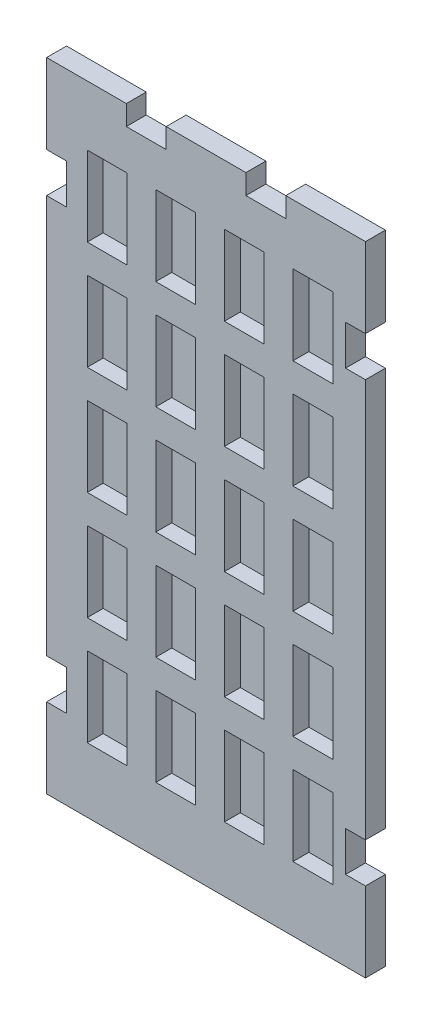
SolidWorks part; units mm, degrees
ref_plane "Front Plane" through (0, 0, 0) normal (0, 0, 1) x (1, 0, 0)
ref_plane "Top Plane" through (0, 0, 0) normal (0, 1, 0) x (1, 0, 0)
ref_plane "Right Plane" through (0, 0, 0) normal (1, 0, 0) x (0, 0, -1)
sketch "Sketch1" plane through (0, 0, 0) normal (0, 0, 1) x (1, 0, 0)
  line L0 (12.7, -101.6) -> (63.5, -101.6)
  line L1 (0, 0) -> (50.8, 0)
  line L2 (0, 0) -> (0, -101.6)
  line L3 (0, -101.6) -> (12.7, -101.6)
  line L4 (50.8, 0) -> (50.8, -101.6)
  line L5 (12.7, 0) -> (19.05, 0)
  line L6 (12.7, 0) -> (12.7, -3.175)
  line L7 (12.7, -3.175) -> (19.05, -3.175)
  line L8 (19.05, 0) -> (19.05, -3.175)
  line L9 (31.75, 0) -> (38.1, 0)
  line L10 (31.75, 0) -> (31.75, -3.175)
  line L11 (31.75, -3.175) -> (38.1, -3.175)
  line L12 (38.1, 0) -> (38.1, -3.175)
  line L13 (50.8, -12.7) -> (47.625, -12.7)
  line L14 (50.8, -12.7) -> (50.8, -19.05)
  line L15 (50.8, -19.05) -> (47.625, -19.05)
  line L16 (47.625, -12.7) -> (47.625, -19.05)
  line L17 (50.8, -82.55) -> (47.625, -82.55)
  line L18 (50.8, -82.55) -> (50.8, -88.9)
  line L19 (50.8, -88.9) -> (47.625, -88.9)
  line L20 (47.625, -82.55) -> (47.625, -88.9)
  line L25 (63.5, -101.6) -> (50.8, -101.6)
  line L29 (0, -88.9) -> (3.175, -88.9)
  line L30 (0, -88.9) -> (0, -82.55)
  line L31 (0, -82.55) -> (3.175, -82.55)
  line L32 (3.175, -88.9) -> (3.175, -82.55)
  line L33 (0, -19.05) -> (3.175, -19.05)
  line L34 (0, -19.05) -> (0, -12.7)
  line L35 (0, -12.7) -> (3.175, -12.7)
  line L36 (3.175, -19.05) -> (3.175, -12.7)
  dimension "D1" = 50.8
  dimension "D2" = 101.6
  dimension "D3" = 12.7
  dimension "D4" = 6.35
  dimension "D5" = 3.175
  dimension "D6" = 6.35
  dimension "D7" = 3.175
  dimension "D8" = 12.7
  dimension "D9" = 12.7
  dimension "D10" = 6.35
  dimension "D11" = 3.175
  dimension "D12" = 3.175
  dimension "D13" = 6.35
  dimension "D14" = 12.7
  dimension "D21" = 3.175
  dimension "D22" = 6.35
  dimension "D23" = 12.7
  dimension "D24" = 12.7
  dimension "D25" = 6.35
  dimension "D26" = 3.175
extrude "Boss-Extrude1" add sketch "Sketch1" along normal blind 3.175
sketch "Sketch2" plane through (0, 0, 3.175) normal (0, 0, 1) x (1, 0, 0)
  line L0 (12.7, -3.175) -> (19.05, -3.175) construction
  line L1 (6.477, -9.525) -> (12.827, -9.525)
  line L2 (6.477, -9.525) -> (6.477, -22.225)
  line L3 (6.477, -22.225) -> (12.827, -22.225)
  line L4 (12.827, -9.525) -> (12.827, -22.225)
  line L5 (6.477, -9.525) -> (12.827, -22.225) construction
  line L6 (6.477, -22.225) -> (12.827, -9.525) construction
  line L7 (3.175, -19.05) -> (3.175, -12.7) construction
  point P0 (9.652, -15.875)
  dimension "D1" = 6.35
  dimension "D2" = 3.302
  dimension "D3" = 6.35
  dimension "D4" = 12.7
extrude "Cut-Extrude1" cut sketch "Sketch2" against normal blind 2.54
pattern_linear "LPattern1" count 4 spacing 10.922 along (1, 0, 0) count 5 spacing 17.272 along (0, -1, 0) of "Cut-Extrude1"
